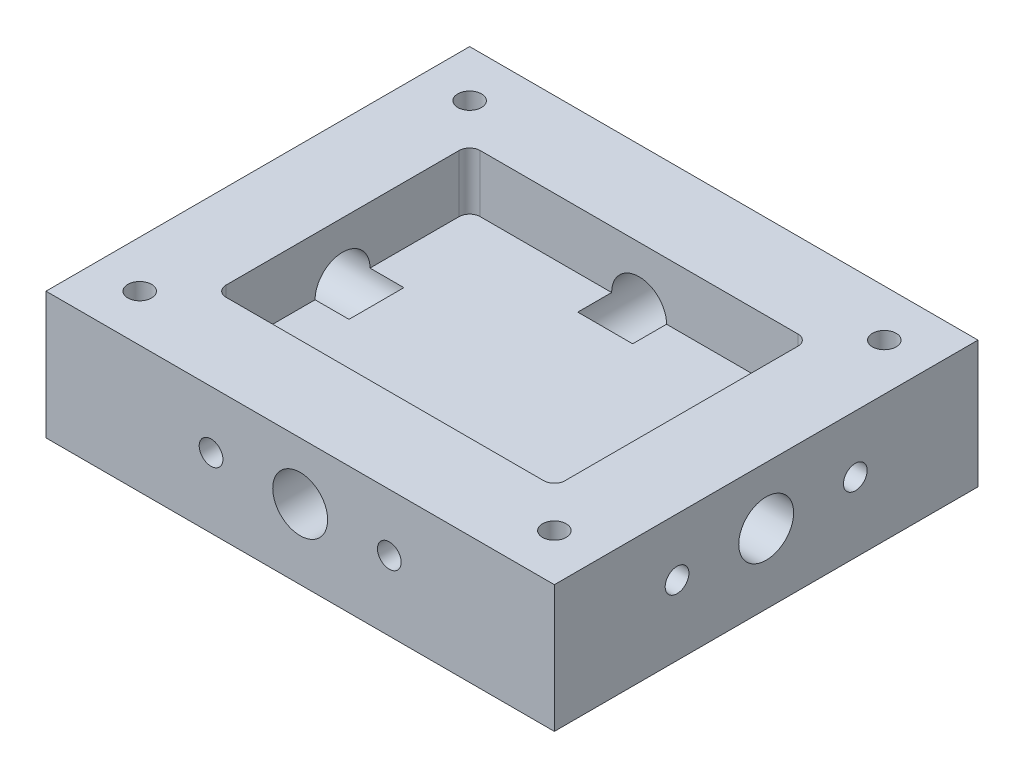
SolidWorks part; units mm, degrees
ref_plane "Front Plane" through (0, 0, 0) normal (0, 0, 1) x (1, 0, 0)
ref_plane "Top Plane" through (0, 0, 0) normal (0, 1, 0) x (1, 0, 0)
ref_plane "Right Plane" through (0, 0, 0) normal (1, 0, 0) x (0, 0, -1)
sketch "Sketch1" plane through (0, 0, 0) normal (0, 1, 0) x (1, 0, 0)
  line L1 (-19.05, -15.875) -> (19.05, -15.875)
  line L2 (-19.05, -15.875) -> (-19.05, 15.875)
  line L3 (-19.05, 15.875) -> (19.05, 15.875)
  line L4 (19.05, -15.875) -> (19.05, 15.875)
  line L5 (-19.05, -15.875) -> (19.05, 15.875) construction
  line L6 (-19.05, 15.875) -> (19.05, -15.875) construction
  point P0 (0, 0)
  dimension "D1" = 31.75
  dimension "D2" = 38.1
extrude "Boss-Extrude1" add sketch "Sketch1" along normal blind 9.525
sketch "Sketch2" plane through (0, 9.525, 0) normal (0, 1, 0) x (1, 0, 0)
  line L1 (-11.9062, -9.525) -> (11.9063, -9.525)
  line L2 (-12.7, -8.7313) -> (-12.7, 8.7312)
  line L3 (-11.9062, 9.525) -> (11.9063, 9.525)
  line L4 (12.7, -8.7313) -> (12.7, 8.7312)
  arc A1 (12.7, 8.7312) -> (11.9063, 9.525) centre (11.9063, 8.7312) ccw
  arc A2 (11.9063, -9.525) -> (12.7, -8.7313) centre (11.9063, -8.7313) ccw
  arc A3 (-12.7, -8.7313) -> (-11.9062, -9.525) centre (-11.9062, -8.7313) ccw
  arc A6 (-11.9062, 9.525) -> (-12.7, 8.7312) centre (-11.9062, 8.7312) ccw
  point P0 (0, 0)
  point P1 (12.7, 9.525)
  point P2 (-12.7, -9.525)
  point P3 (-12.7, 9.525)
  point P4 (12.7, -9.525)
  point P22 (0, 0)
  dimension "D2" = 19.05
extrude "Cut-Extrude2" cut sketch "Sketch2" against normal blind 4.2926 contours A3 L1 A2 L4 A1 L3 A6 L2
sketch "Sketch3" plane through (-19.05, 0, 0) normal (-1, 0, 0) x (0, 0, 1)
  circle A0 centre (0, 5.2324) radius 2.0574
  dimension "D1" = 4.1148
extrude "Cut-Extrude3" cut sketch "Sketch3" against normal blind 8.89
mirror "Mirror1" about plane through (0, 0, 0) normal (1, 0, 0) of "Cut-Extrude3"
sketch "Sketch7" plane through (0, 0, -15.875) normal (0, 0, -1) x (-1, 0, 0)
  circle A0 centre (0, 5.2324) radius 2.0574
  point P2 (0, 0)
  dimension "D1" = 4.1148
extrude "Cut-Extrude5" cut sketch "Sketch7" against normal blind 8.89
mirror "Mirror2" about plane through (0, 0, 0) normal (0, 0, 1) of "Cut-Extrude5"
sketch "Sketch8" plane through (19.05, 0, 0) normal (1, 0, 0) x (0, 0, -1)
  circle A0 centre (6.6802, 5.2324) radius 0.889
  dimension "D1" = 1.778
extrude "Cut-Extrude6" cut sketch "Sketch8" against normal blind 4.7625
mirror "Mirror3" about plane through (0, 0, 0) normal (0, 0, 1) of "Cut-Extrude6"
mirror "Mirror4" about plane through (0, 0, 0) normal (1, 0, 0) of "Mirror3", "Cut-Extrude6"
sketch "Sketch11" plane through (0, 0, 15.875) normal (0, 0, 1) x (1, 0, 0)
  line L0 (-2.0574, 5.2324) -> (2.0574, 5.2324) construction
  circle A0 centre (6.6802, 5.2324) radius 0.889
extrude "Cut-Extrude7" cut sketch "Sketch11" against normal blind 4.7625
mirror "Mirror5" about plane through (0, 0, 0) normal (1, 0, 0) of "Cut-Extrude7"
mirror "Mirror6" about plane through (0, 0, 0) normal (0, 0, 1) of "Mirror5", "Cut-Extrude7"
sketch "Sketch12" plane through (0, 9.525, 0) normal (0, 1, 0) x (1, 0, 0)
  circle A0 centre (-15.5385, 12.3635) radius 0.889
  circle A1 centre (15.5385, 12.3635) radius 0.889
  circle A2 centre (-15.5385, -12.3635) radius 0.889
  circle A3 centre (15.5385, -12.3635) radius 0.889
extrude "Cut-Extrude9" cut sketch "Sketch12" against normal blind 7.9375
